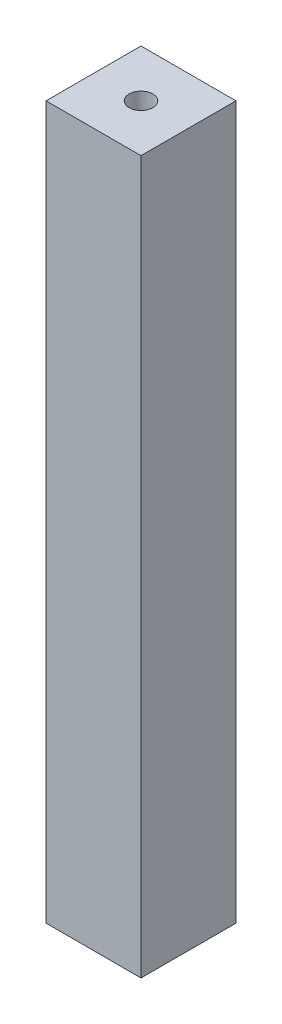
SolidWorks part; units mm, degrees
ref_plane "Front Plane" through (0, 0, 0) normal (0, 0, 1) x (1, 0, 0)
ref_plane "Top Plane" through (0, 0, 0) normal (0, 1, 0) x (1, 0, 0)
ref_plane "Right Plane" through (0, 0, 0) normal (1, 0, 0) x (0, 0, -1)
sketch "Sketch1" plane through (0, 0, 0) normal (0, 1, 0) x (1, 0, 0)
  line L1 (10, -10) -> (-10, -10)
  line L2 (10, -10) -> (10, 10)
  line L3 (10, 10) -> (-10, 10)
  line L4 (-10, -10) -> (-10, 10)
  line L5 (10, -10) -> (-10, 10) construction
  line L6 (10, 10) -> (-10, -10) construction
  point P0 (0, 0)
  dimension "D1" = 20
  dimension "D2" = 20
extrude "Boss-Extrude1" add sketch "Sketch1" along normal blind 150
sketch "Sketch2" plane through (0, 150, 0) normal (0, 1, 0) x (1, 0, 0)
  circle A0 centre (0, 0) radius 2.5
extrude "Cut-Extrude1" cut sketch "Sketch2" against normal blind 150
